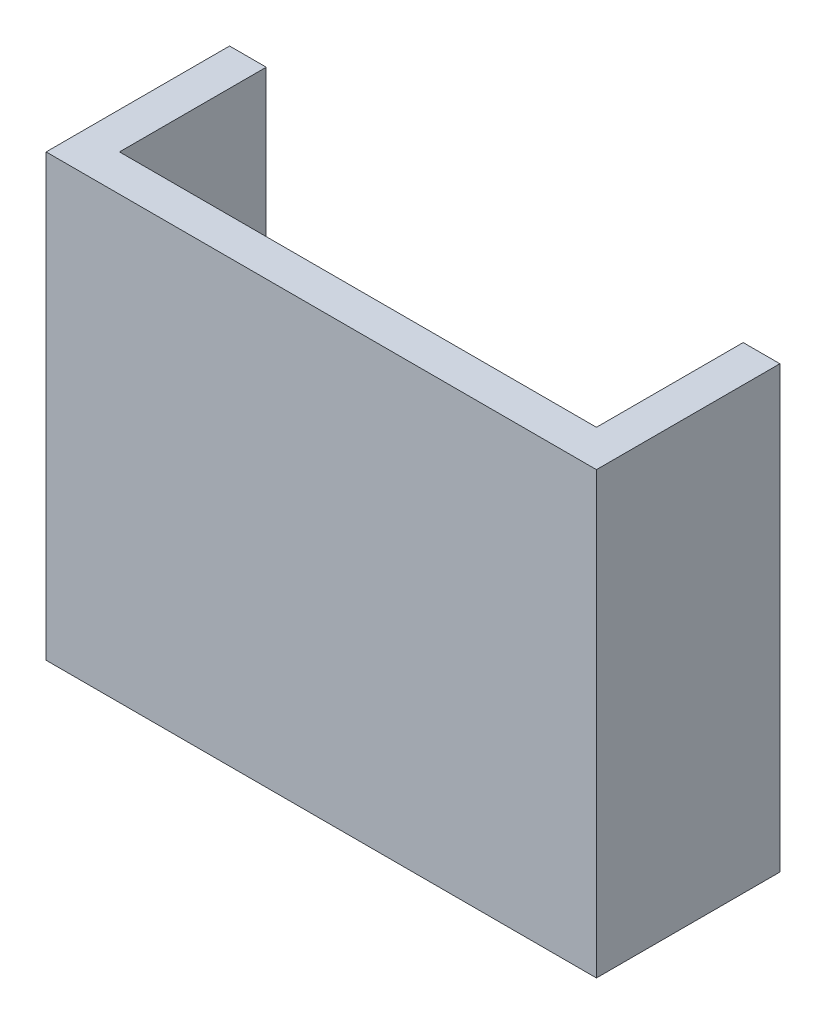
SolidWorks part; units mm, degrees
ref_plane "前基準面" through (0, 0, 0) normal (0, 0, 1) x (1, 0, 0)
ref_plane "上基準面" through (0, 0, 0) normal (0, 1, 0) x (1, 0, 0)
ref_plane "右基準面" through (0, 0, 0) normal (1, 0, 0) x (0, 0, -1)
sketch "草圖1" plane through (0, 0, 0) normal (0, 0, 1) x (1, 0, 0)
  line L1 (-30, 24) -> (0, 24)
  line L2 (-30, 24) -> (-30, 0)
  line L3 (-30, 0) -> (0, 0)
  line L4 (0, 24) -> (0, 0)
  dimension "D1" = 30
  dimension "D2" = 24
extrude "填料-伸長1" add sketch "草圖1" along normal blind 10
sketch "草圖2" plane through (0, 0, 0) normal (0, 0, -1) x (-1, 0, 0)
  line L0 (30, 0) -> (0, 0) construction
  line L1 (28, 24) -> (2, 24)
  line L2 (28, 24) -> (28, 0)
  line L3 (28, 0) -> (2, 0)
  line L4 (2, 24) -> (2, 0)
  line L5 (0, 0) -> (0, 24) construction
  line L6 (30, 24) -> (30, 0) construction
  dimension "D1" = 24
  dimension "D2" = 0
  dimension "D3" = 2
  dimension "D4" = 2
extrude "除料-伸長1" cut sketch "草圖2" against normal blind 8
